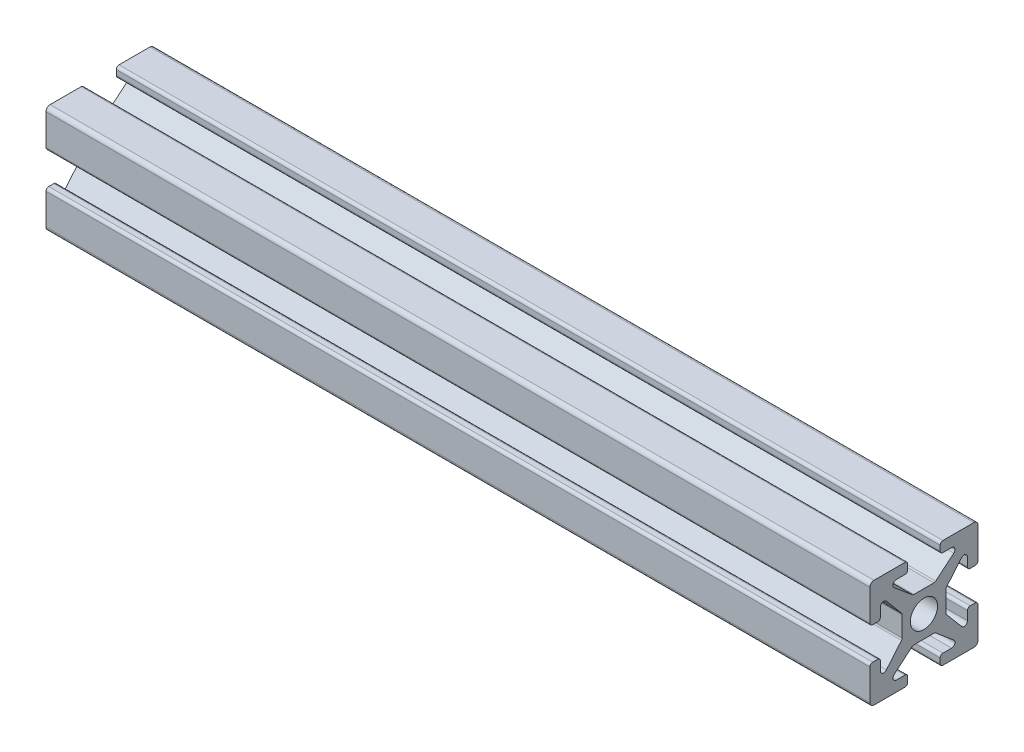
SolidWorks part; units mm, degrees
ref_plane "Front Plane" through (0, 0, 0) normal (0, 0, 1) x (1, 0, 0)
ref_plane "Top Plane" through (0, 0, 0) normal (0, 1, 0) x (1, 0, 0)
ref_plane "Right Plane" through (0, 0, 0) normal (1, 0, 0) x (0, 0, -1)
sketch "Sketch1" plane through (0, 0, 0) normal (1, 0, 0) x (0, 0, -1)
  line L0 (0, 5) -> (0, -5) construction
  line L1 (-5, 5) -> (5, 5)
  line L2 (-5, 5) -> (-5, -5)
  line L3 (-5, -5) -> (5, -5)
  line L4 (5, 5) -> (5, -5)
  line L5 (-5, 0) -> (5, 0) construction
  line L6 (-1.019, 2.0193) -> (1.019, 2.0193)
  line L7 (1.019, 2.0193) -> (2.7598, 3.4799)
  line L8 (2.8702, 3.7168) -> (-2.8702, 3.7168) construction
  circle A0 centre (0, 0) radius 1.2573
  arc A1 (2.7598, 3.4799) -> (2.5611, 4.0259) centre (2.5611, 3.7168) ccw
  arc A2 (4.619, 5) -> (5, 4.619) centre (4.619, 4.619) cw
  point P8 (0, 0)
  point P10 (1.4986, 5)
  point P17 (0, 2.0193)
  point P19 (0, 1.2573)
  point P20 (-1.4986, 5)
  point P27 (1.4948, 5)
  dimension "D1" = 2.5146
  dimension "D5" = 0.381
  dimension "Rail Width" = 10
  dimension "Rail Height" = 10
  dimension "T-Slot Width" = 2.9972
  dimension "D2" = 0.762
  dimension "D3" = 2.0066
  dimension "D4" = 5.7404
  dimension "D6" = 3.5052
  dimension "D7" = 40
  dimension "D8" = 2.0381
sketch "Sketch2" plane through (0, 0, 0) normal (0, 0, 1) x (1, 0, 0)
  line L0 (-38.1, 0) -> (38.1, 0)
  line L1 (-38.1, 5) -> (38.1, 5) construction
  point P0 (-23.1, 0)
  point P4 (0, 0)
  point P5 (23.1, 0)
  dimension "Length" = 76.2
  dimension "D1" = 15
  dimension "D2" = 15
sketch "Sketch4" plane through (0, 0, 0) normal (1, 0, 0) x (0, 0, -1)
  line L0 (-5, 0) -> (5, 0) construction
  line L1 (0, 1.2573) -> (0, 2.0193)
  line L2 (0, 2.0193) -> (0.9266, 2.0193)
  line L3 (1.0899, 2.0787) -> (2.7598, 3.4799)
  line L4 (2.5611, 4.0259) -> (1.7526, 4.0259)
  line L5 (1.4986, 4.2799) -> (1.4986, 4.746)
  line L6 (1.7526, 5) -> (4.619, 5)
  line L7 (0, 0) -> (5, 5) construction
  line L9 (5, 1.7526) -> (5, 4.619)
  line L10 (4.2799, 1.4986) -> (4.746, 1.4986)
  line L11 (4.0259, 2.5611) -> (4.0259, 1.7526)
  line L12 (2.0787, 1.0899) -> (3.4799, 2.7598)
  line L13 (2.0193, 0) -> (2.0193, 0.9266)
  line L14 (1.2573, 0) -> (2.0193, 0)
  arc A0 (0, 1.2573) -> (1.2573, 0) centre (0, 0) cw
  circle A1 centre (0, 0) radius 1.2573 construction
  arc A2 (2.7598, 3.4799) -> (2.5611, 4.0259) centre (2.5611, 3.7168) ccw construction
  arc A3 (2.7598, 3.4799) -> (2.5611, 4.0259) centre (2.5611, 3.7168) ccw
  arc A4 (5, 4.619) -> (4.619, 5) centre (4.619, 4.619) ccw construction
  arc A5 (5, 4.619) -> (4.619, 5) centre (4.619, 4.619) ccw
  arc A6 (0.9266, 2.0193) -> (1.0899, 2.0787) centre (0.9266, 2.2733) ccw
  arc A7 (1.7526, 5) -> (1.4986, 4.746) centre (1.7526, 4.746) ccw
  arc A8 (1.4986, 4.2799) -> (1.7526, 4.0259) centre (1.7526, 4.2799) ccw
  arc A9 (5, 1.7526) -> (4.746, 1.4986) centre (4.746, 1.7526) cw
  arc A10 (4.2799, 1.4986) -> (4.0259, 1.7526) centre (4.2799, 1.7526) cw
  arc A11 (3.4799, 2.7598) -> (4.0259, 2.5611) centre (3.7168, 2.5611) cw
  arc A12 (2.0193, 0.9266) -> (2.0787, 1.0899) centre (2.2733, 0.9266) cw
  point P26 (1.019, 2.0193)
  point P30 (1.4986, 5)
  dimension "D1" = 0.254
extrude "Boss-Extrude1" add sketch "Sketch4" along normal up to vertex (38.1 mm away) from vertex at -38.1 starting at point (-38.1, 0, 0)
mirror "Mirror1" about plane through (0, 0, 0) normal (0, 1, 0) of bodies 104
mirror "Mirror2" about plane through (0, 0, 0) normal (0, 0, 1) of bodies 105
equation "\"D8@Sketch1\"=\"T-Slot Width@Sketch1\"*.68"
equation "\"D1@Sketch2\"=\"Rail Width@Sketch1\"*1.5"
equation "\"D2@Sketch2\"=\"D1@Sketch2\""
